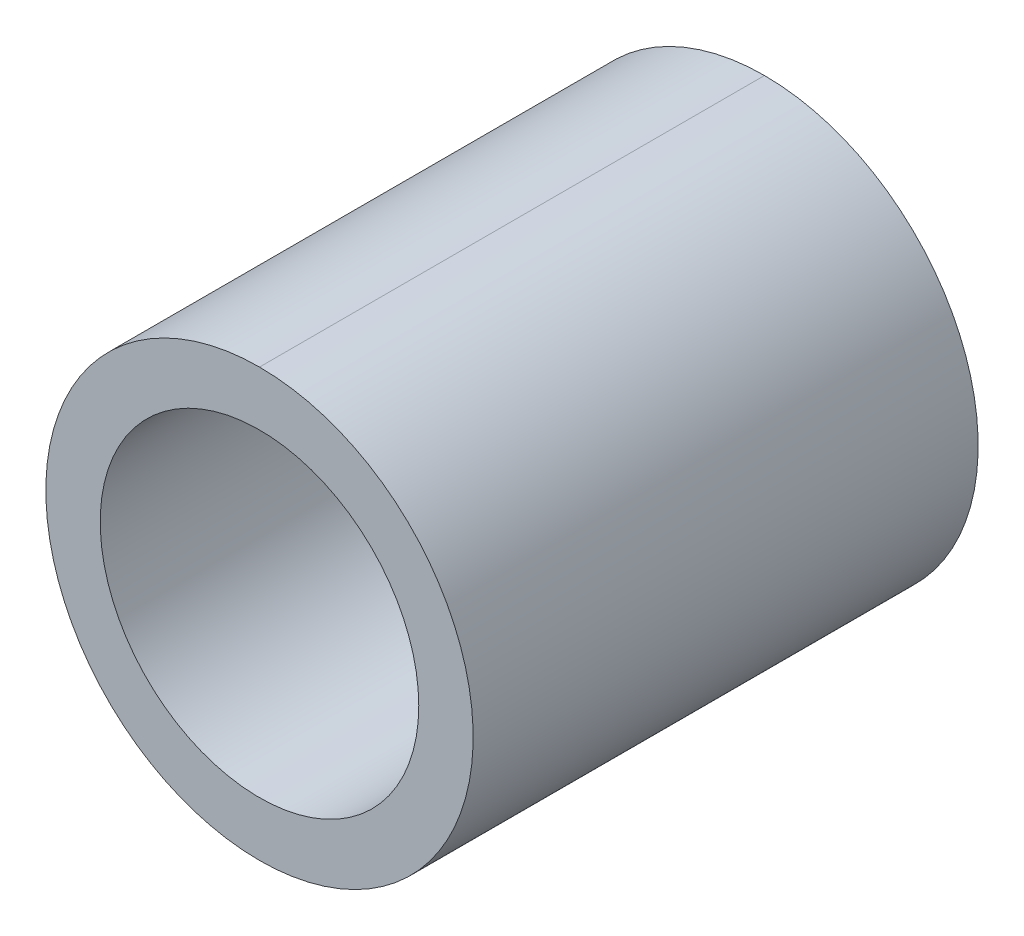
SolidWorks part; units mm, degrees
ref_plane "Front Plane" through (0, 0, 0) normal (0, 0, 1) x (1, 0, 0)
ref_plane "Top Plane" through (0, 0, 0) normal (0, 1, 0) x (1, 0, 0)
ref_plane "Right Plane" through (0, 0, 0) normal (1, 0, 0) x (0, 0, -1)
sketch "Sketch1" plane through (0, 0, 0) normal (0, 0, 1) x (1, 0, 0)
  circle A0 centre (0, 0) radius 55
  dimension "D1" = 110
extrude "Boss-Extrude1" add sketch "Sketch1" along normal blind 130
sketch "Sketch2" plane through (0, 0, 130) normal (0, 0, 1) x (1, 0, 0)
  circle A0 centre (0, 0) radius 41
  circle A1 centre (0, 0) radius 55 construction
  dimension "D1" = 14
extrude "Cut-Extrude1" cut sketch "Sketch2" against normal blind 120
ref_plane "Plane1" through (0, -55, 0) normal (0, -1, 0) x (-1, 0, 0)
sketch "Sketch4" plane through (0, -55, 0) normal (0, -1, 0) x (-1, 0, 0)
  line L0 (0, 0) -> (0, -130)
  line L1 (-55, -130) -> (55, -130) construction
split line "Split Line1"
